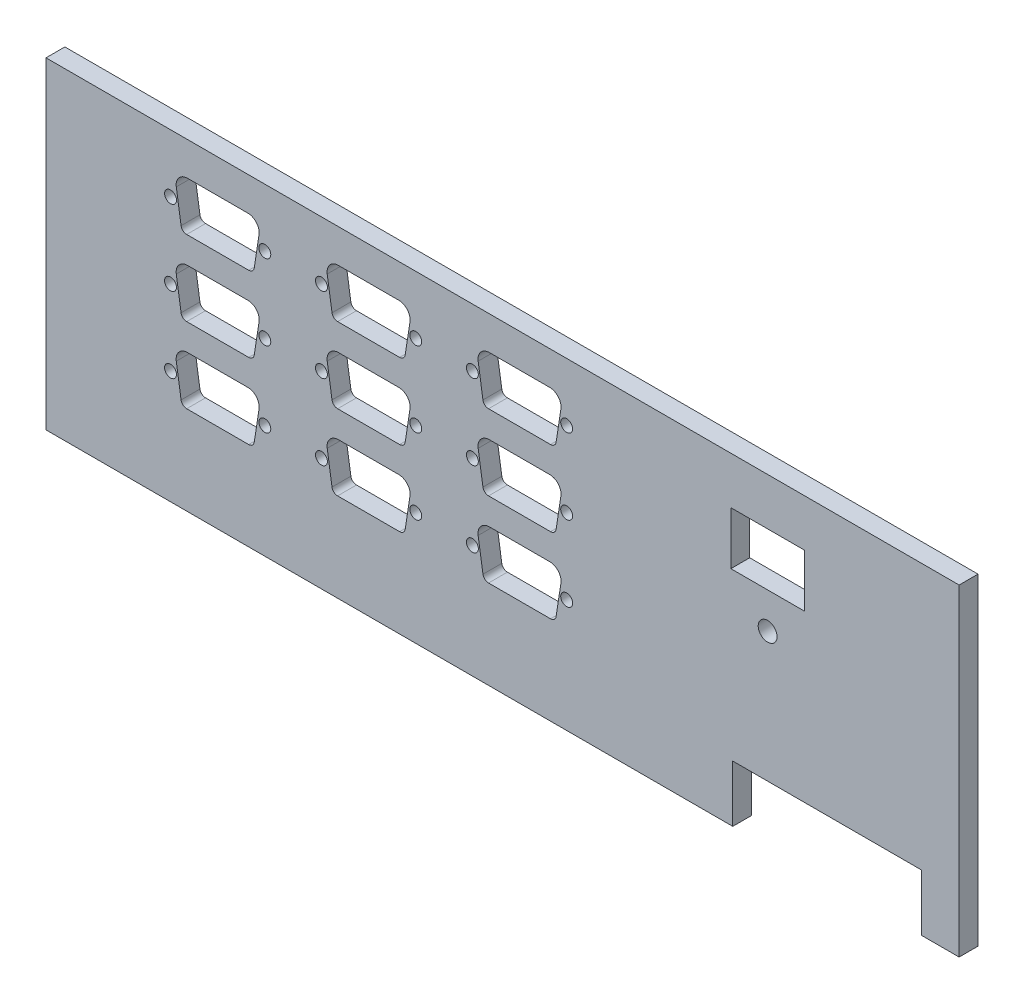
SolidWorks part; units mm, degrees
ref_plane "Front Plane" through (0, 0, 0) normal (0, 0, 1) x (1, 0, 0)
ref_plane "Top Plane" through (0, 0, 0) normal (0, 1, 0) x (1, 0, 0)
ref_plane "Right Plane" through (0, 0, 0) normal (1, 0, 0) x (0, 0, -1)
sketch "Sketch1" plane through (0, 0, 0) normal (0, 0, 1) x (1, 0, 0)
  line L1 (0, 0) -> (239, 0)
  line L2 (0, 0) -> (0, 85.4)
  line L3 (0, 85.4) -> (239, 85.4)
  line L4 (239, 0) -> (239, 85.4)
  dimension "D1" = 85.4
  dimension "D2" = 239
extrude "Boss-Extrude1" add sketch "Sketch1" along normal blind 5
sketch "Sketch2" plane through (0, 0, 5) normal (0, 0, 1) x (1, 0, 0)
  line L0 (0, 0) -> (239, 0) construction
  line L1 (0, 85.4) -> (0, 0) construction
  circle A0 centre (30, 30) radius 1.58
  circle A1 centre (54.99, 30) radius 1.58
  circle A2 centre (94.99, 30) radius 1.58
  circle A3 centre (70, 30) radius 1.58
  circle A4 centre (134.99, 30) radius 1.58
  circle A5 centre (110, 30) radius 1.58
  circle A6 centre (94.99, 50) radius 1.58
  circle A7 centre (70, 50) radius 1.58
  circle A8 centre (134.99, 50) radius 1.58
  circle A9 centre (110, 50) radius 1.58
  circle A10 centre (94.99, 70) radius 1.58
  circle A11 centre (70, 70) radius 1.58
  circle A12 centre (134.99, 70) radius 1.58
  circle A13 centre (110, 70) radius 1.58
  circle A14 centre (54.99, 50) radius 1.58
  circle A15 centre (30, 50) radius 1.58
  circle A16 centre (54.99, 70) radius 1.58
  circle A17 centre (30, 70) radius 1.58
  dimension "D2" = 3.16
  dimension "D1" = 24.99
  dimension "D3" = 30
  dimension "D4" = 30
  dimension "D5" = 3
  dimension "D6" = 3
extrude "Cut-Extrude1" cut sketch "Sketch2" against normal through all
sketch "Sketch3" plane through (0, 0, 5) normal (0, 0, 1) x (1, 0, 0)
  line L0 (31.5267, 33.0438) -> (32.7993, 24.7719)
  line L1 (34.2819, 23.5) -> (50.7081, 23.5)
  line L2 (52.1907, 24.7719) -> (53.4633, 33.0438)
  line L3 (50.4982, 36.5) -> (34.4918, 36.5)
  line L4 (71.5267, 33.0438) -> (72.7993, 24.7719)
  line L5 (74.2819, 23.5) -> (90.7081, 23.5)
  line L6 (92.1907, 24.7719) -> (93.4633, 33.0438)
  line L7 (90.4982, 36.5) -> (74.4918, 36.5)
  line L8 (111.5267, 33.0438) -> (112.7993, 24.7719)
  line L9 (114.2819, 23.5) -> (130.7081, 23.5)
  line L10 (132.1907, 24.7719) -> (133.4633, 33.0438)
  line L11 (130.4982, 36.5) -> (114.4918, 36.5)
  line L12 (71.5267, 53.0438) -> (72.7993, 44.7719)
  line L13 (74.2819, 43.5) -> (90.7081, 43.5)
  line L14 (92.1907, 44.7719) -> (93.4633, 53.0438)
  line L15 (90.4982, 56.5) -> (74.4918, 56.5)
  line L16 (111.5267, 53.0438) -> (112.7993, 44.7719)
  line L17 (114.2819, 43.5) -> (130.7081, 43.5)
  line L18 (132.1907, 44.7719) -> (133.4633, 53.0438)
  line L19 (130.4982, 56.5) -> (114.4918, 56.5)
  line L20 (71.5267, 73.0438) -> (72.7993, 64.7719)
  line L21 (74.2819, 63.5) -> (90.7081, 63.5)
  line L22 (92.1907, 64.7719) -> (93.4633, 73.0438)
  line L23 (90.4982, 76.5) -> (74.4918, 76.5)
  line L24 (111.5267, 73.0438) -> (112.7993, 64.7719)
  line L25 (114.2819, 63.5) -> (130.7081, 63.5)
  line L26 (132.1907, 64.7719) -> (133.4633, 73.0438)
  line L27 (130.4982, 76.5) -> (114.4918, 76.5)
  line L28 (31.5267, 53.0438) -> (32.7993, 44.7719)
  line L29 (34.2819, 43.5) -> (50.7081, 43.5)
  line L30 (52.1907, 44.7719) -> (53.4633, 53.0438)
  line L31 (50.4982, 56.5) -> (34.4918, 56.5)
  line L32 (31.5267, 73.0438) -> (32.7993, 64.7719)
  line L33 (34.2819, 63.5) -> (50.7081, 63.5)
  line L34 (52.1907, 64.7719) -> (53.4633, 73.0438)
  line L35 (50.4982, 76.5) -> (34.4918, 76.5)
  circle A0 centre (54.99, 30) radius 1.58 construction
  circle A1 centre (30, 30) radius 1.58 construction
  arc A2 (53.4633, 33.0438) -> (50.4982, 36.5) centre (50.4982, 33.5) ccw
  arc A3 (34.4918, 36.5) -> (31.5267, 33.0438) centre (34.4918, 33.5) ccw
  arc A4 (50.7081, 23.5) -> (52.1907, 24.7719) centre (50.7081, 25) ccw
  arc A5 (34.2819, 23.5) -> (32.7993, 24.7719) centre (34.2819, 25) cw
  arc A6 (93.4633, 33.0438) -> (90.4982, 36.5) centre (90.4982, 33.5) ccw
  arc A7 (74.4918, 36.5) -> (71.5267, 33.0438) centre (74.4918, 33.5) ccw
  arc A8 (90.7081, 23.5) -> (92.1907, 24.7719) centre (90.7081, 25) ccw
  arc A9 (74.2819, 23.5) -> (72.7993, 24.7719) centre (74.2819, 25) cw
  arc A10 (133.4633, 33.0438) -> (130.4982, 36.5) centre (130.4982, 33.5) ccw
  arc A11 (114.4918, 36.5) -> (111.5267, 33.0438) centre (114.4918, 33.5) ccw
  arc A12 (130.7081, 23.5) -> (132.1907, 24.7719) centre (130.7081, 25) ccw
  arc A13 (114.2819, 23.5) -> (112.7993, 24.7719) centre (114.2819, 25) cw
  arc A14 (93.4633, 53.0438) -> (90.4982, 56.5) centre (90.4982, 53.5) ccw
  arc A15 (74.4918, 56.5) -> (71.5267, 53.0438) centre (74.4918, 53.5) ccw
  arc A16 (90.7081, 43.5) -> (92.1907, 44.7719) centre (90.7081, 45) ccw
  arc A17 (74.2819, 43.5) -> (72.7993, 44.7719) centre (74.2819, 45) cw
  arc A18 (133.4633, 53.0438) -> (130.4982, 56.5) centre (130.4982, 53.5) ccw
  arc A19 (114.4918, 56.5) -> (111.5267, 53.0438) centre (114.4918, 53.5) ccw
  arc A20 (130.7081, 43.5) -> (132.1907, 44.7719) centre (130.7081, 45) ccw
  arc A21 (114.2819, 43.5) -> (112.7993, 44.7719) centre (114.2819, 45) cw
  arc A22 (93.4633, 73.0438) -> (90.4982, 76.5) centre (90.4982, 73.5) ccw
  arc A23 (74.4918, 76.5) -> (71.5267, 73.0438) centre (74.4918, 73.5) ccw
  arc A24 (90.7081, 63.5) -> (92.1907, 64.7719) centre (90.7081, 65) ccw
  arc A25 (74.2819, 63.5) -> (72.7993, 64.7719) centre (74.2819, 65) cw
  arc A26 (133.4633, 73.0438) -> (130.4982, 76.5) centre (130.4982, 73.5) ccw
  arc A27 (114.4918, 76.5) -> (111.5267, 73.0438) centre (114.4918, 73.5) ccw
  arc A28 (130.7081, 63.5) -> (132.1907, 64.7719) centre (130.7081, 65) ccw
  arc A29 (114.2819, 63.5) -> (112.7993, 64.7719) centre (114.2819, 65) cw
  arc A30 (53.4633, 53.0438) -> (50.4982, 56.5) centre (50.4982, 53.5) ccw
  arc A31 (34.4918, 56.5) -> (31.5267, 53.0438) centre (34.4918, 53.5) ccw
  arc A32 (50.7081, 43.5) -> (52.1907, 44.7719) centre (50.7081, 45) ccw
  arc A33 (34.2819, 43.5) -> (32.7993, 44.7719) centre (34.2819, 45) cw
  arc A34 (53.4633, 73.0438) -> (50.4982, 76.5) centre (50.4982, 73.5) ccw
  arc A35 (34.4918, 76.5) -> (31.5267, 73.0438) centre (34.4918, 73.5) ccw
  arc A36 (50.7081, 63.5) -> (52.1907, 64.7719) centre (50.7081, 65) ccw
  arc A37 (34.2819, 63.5) -> (32.7993, 64.7719) centre (34.2819, 65) cw
  point P2 (42.495, 36.5)
  point P7 (42.495, 23.5)
  point P12 (53.995, 36.5)
  point P15 (30.995, 36.5)
  point P18 (51.995, 23.5)
  point P21 (32.995, 23.5)
  dimension "D7" = 3
  dimension "D8" = 1.5
  dimension "D1" = 13
  dimension "D2" = 12.495
  dimension "D3" = 23
  dimension "D4" = 19
  dimension "D5" = 12.495
  dimension "D6" = 6.5
  dimension "D9" = 3
  dimension "D10" = 3
extrude "Cut-Extrude2" cut sketch "Sketch3" against normal through all
sketch "Sketch4" plane through (0, 0, 5) normal (0, 0, 1) x (1, 0, 0)
  line L0 (0, 0) -> (239, 0) construction
  line L1 (179, 15) -> (229, 15)
  line L2 (179, 15) -> (179, 0)
  line L3 (179, 0) -> (229, 0)
  line L4 (229, 15) -> (229, 0)
  line L5 (239, 0) -> (239, 85.4) construction
  line L6 (239, 85.4) -> (0, 85.4) construction
  line L7 (178.5, 72.9) -> (198, 72.9)
  line L8 (178.5, 72.9) -> (178.5, 58.9)
  line L9 (178.5, 58.9) -> (198, 58.9)
  line L10 (198, 72.9) -> (198, 58.9)
  circle A0 centre (188.25, 49.4) radius 2.5
  dimension "D8" = 5
  dimension "D1" = 15
  dimension "D2" = 50
  dimension "D3" = 10
  dimension "D4" = 14
  dimension "D5" = 19.5
  dimension "D6" = 12.5
  dimension "D7" = 41
  dimension "D9" = 36
  dimension "D10" = 9.75
extrude "Cut-Extrude3" cut sketch "Sketch4" against normal through all
sketch "Sketch5" plane through (0, 0, 0) normal (-1, 0, 0) x (0, 0, 1)
  line L1 (0, 85.4) -> (5, 85.4)
  line L2 (0, 85.4) -> (0, 0)
  line L3 (0, 0) -> (5, 0)
  line L4 (5, 85.4) -> (5, 0)
extrude "Boss-Extrude2" add sketch "Sketch5" along normal blind 3
